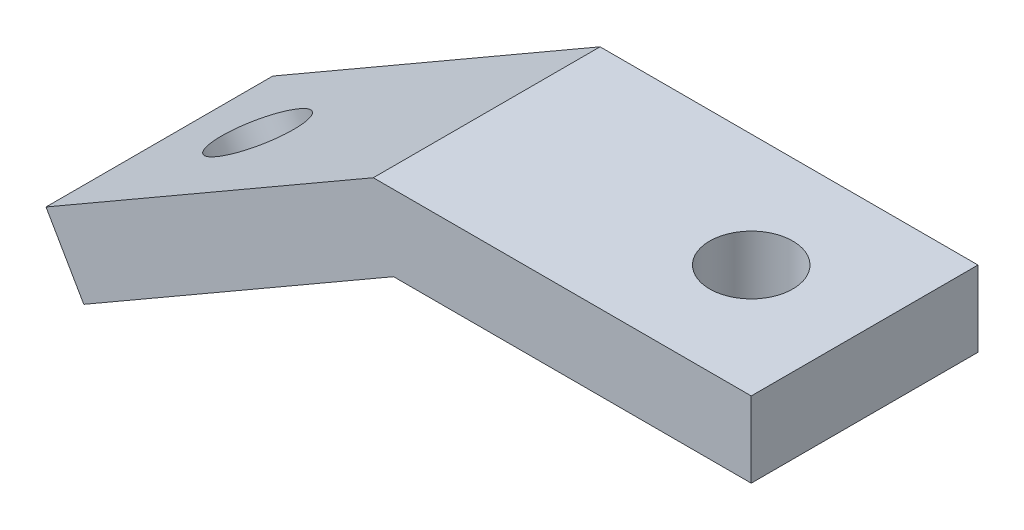
SolidWorks part; units mm, degrees
ref_plane "Front Plane" through (0, 0, 0) normal (0, 0, 1) x (1, 0, 0)
ref_plane "Top Plane" through (0, 0, 0) normal (0, 1, 0) x (1, 0, 0)
ref_plane "Right Plane" through (0, 0, 0) normal (1, 0, 0) x (0, 0, -1)
sketch "Sketch1" plane through (0, 0, 0) normal (0, 0, 1) x (1, 0, 0)
  line L0 (-8.4746, -0.3408) -> (0.1856, 4.6592)
  line L1 (0.1856, 4.6592) -> (10.1856, 4.6592)
  line L2 (10.1856, 4.6592) -> (10.1856, 2.6592)
  line L3 (10.1856, 2.6592) -> (0.7215, 2.6592)
  line L4 (0.7215, 2.6592) -> (-7.4746, -2.0729)
  line L5 (-7.4746, -2.0729) -> (-8.4746, -0.3408)
  dimension "D1" = 10
  dimension "D2" = 10
  dimension "D3" = 150
  dimension "D4" = 2
  dimension "D5" = 2
extrude "Boss-Extrude1" add sketch "Sketch1" along normal blind 6
sketch "Sketch2" plane through (0, 4.6592, 0) normal (0, 1, 0) x (1, 0, 0)
  line L0 (10.1856, 0) -> (0.1856, 0) construction
  line L1 (10.1856, -6) -> (10.1856, 0) construction
  circle A0 centre (7.1856, -3) radius 1.1
  dimension "D1" = 2.2
  dimension "D2" = 3
  dimension "D3" = 3
extrude "Cut-Extrude1" cut sketch "Sketch2" against normal blind 6
sketch "Sketch3" plane through (-1.9711, 3.414, 0) normal (-0.5, 0.866, 0) x (0.866, 0.5, 0)
  line L0 (2.4904, 0) -> (-7.5096, 0) construction
  line L1 (-7.5096, -6) -> (-7.5096, 0) construction
  circle A0 centre (-4.5096, -3) radius 1.1
  dimension "D1" = 2.2
  dimension "D2" = 3
  dimension "D3" = 3
extrude "Cut-Extrude2" cut sketch "Sketch3" against normal blind 6
